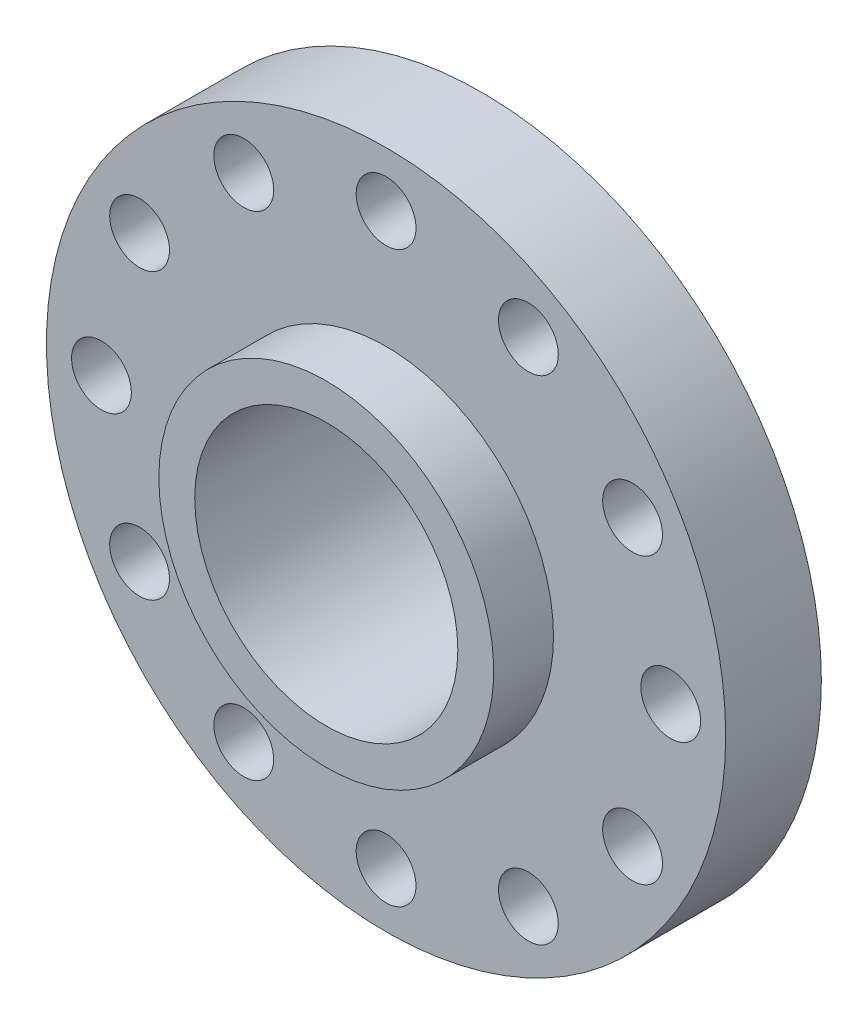
SolidWorks part; units mm, degrees
ref_plane "Front Plane" through (0, 0, 0) normal (0, 0, 1) x (1, 0, 0)
ref_plane "Top Plane" through (0, 0, 0) normal (0, 1, 0) x (1, 0, 0)
ref_plane "Right Plane" through (0, 0, 0) normal (1, 0, 0) x (0, 0, -1)
sketch "Sketch1" plane through (0, 0, 0) normal (0, 0, 1) x (1, 0, 0)
  circle A0 centre (0, 0) radius 11
  circle A1 centre (0, 0) radius 28.4
  dimension "D1" = 22
extrude "Boss-Extrude1" add sketch "Sketch1" along normal blind 8
sketch "Sketch2" plane through (0, 0, 0) normal (0, 0, -1) x (-1, 0, 0)
  circle A0 centre (0, 0) radius 11 construction
  circle A1 centre (0, 0) radius 28.4
  circle A2 centre (0, 0) radius 28.4
  circle A3 centre (0, 0) radius 11
  circle A4 centre (0, 0) radius 14
  circle M3 centre (0, 0) radius 11
  dimension "D2" = 28
  dimension "D1" = 0
extrude "Boss-Extrude2" add sketch "Sketch2" along normal blind 5 contours A4 M3
ref_plane "Plane1" through (0, 0, 4) normal (0, 0, 1) x (1, 0, 0)
mirror "Mirror1" about plane through (0, 0, 4) normal (0, 0, 1) of "Boss-Extrude2"
sketch "Sketch3" plane through (0, 0, 0) normal (0, 0, -1) x (-1, 0, 0)
  circle A0 centre (11.9, 20.6114) radius 2.5
  dimension "D1" = 5
extrude "Cut-Extrude1" cut sketch "Sketch3" against normal through all
pattern_circular "CirPattern1" count 12 over 360 about axis through (0, 0, 0) along (0, 0, 1) of "Cut-Extrude1"
scale "Scale1" scale about centroid uniform scaling yes scale factor 0.24
